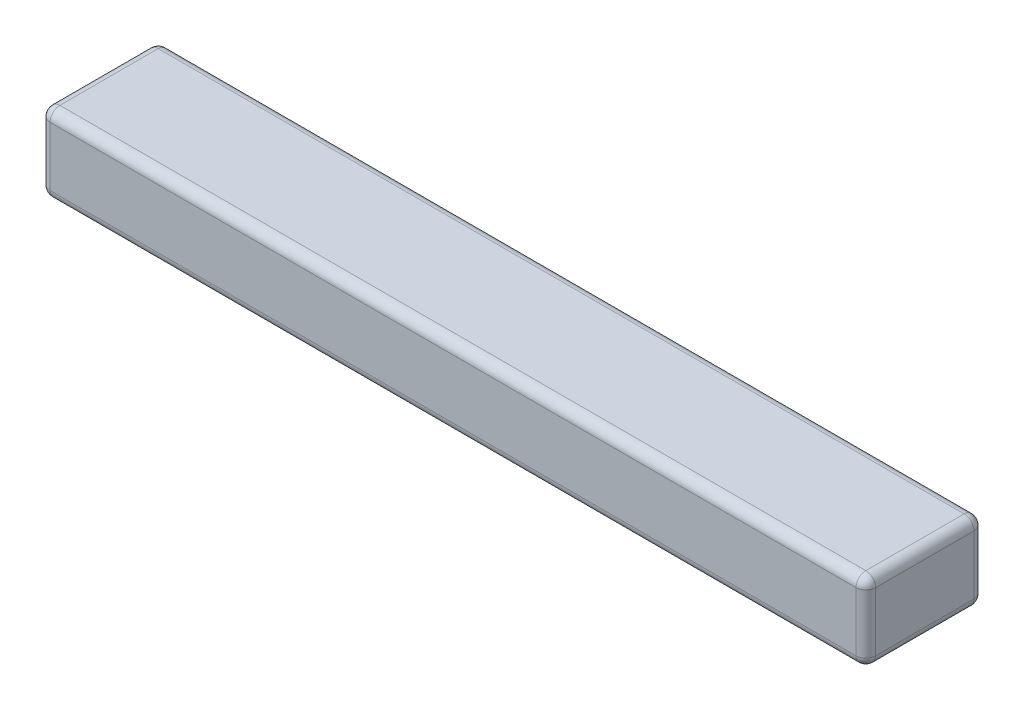
SolidWorks part; units mm, degrees
ref_plane "Front Plane" through (0, 0, 0) normal (0, 0, 1) x (1, 0, 0)
ref_plane "Top Plane" through (0, 0, 0) normal (0, 1, 0) x (1, 0, 0)
ref_plane "Right Plane" through (0, 0, 0) normal (1, 0, 0) x (0, 0, -1)
sketch "Sketch1" plane through (0, 0, 0) normal (1, 0, 0) x (0, 0, -1)
  line L1 (-30, -20) -> (30, -20)
  line L2 (-30, -20) -> (-30, 20)
  line L3 (-30, 20) -> (30, 20)
  line L4 (30, -20) -> (30, 20)
  line L5 (-30, -20) -> (30, 20) construction
  line L6 (-30, 20) -> (30, -20) construction
  point P0 (0, 0)
  dimension "D1" = 60
  dimension "D2" = 40
extrude "Boss-Extrude1" add sketch "Sketch1" along normal mid plane 420
fillet "Fillet1" radius 5 12 edges at (-210, -20, 0) (-210, 0, -30) (-210, 20, 0) (-210, 0, 30) (210, 0, -30) (210, 20, 0) (210, -20, 0) (210, 0, 30) (0, -20, -30) (0, 20, -30) (0, -20, 30) (0, 20, 30)
sketch "Sketch2" plane through (0, 20, 0) normal (0, 1, 0) x (1, 0, 0)
  line L0 (-100, 25) -> (-100, -25) construction
  line L1 (205, 25) -> (-205, 25) construction
  line L2 (-205, -25) -> (205, -25) construction
  line L3 (100, 25) -> (100, -25) construction
  line L4 (-210, -25) -> (-210, 25) construction
  line L5 (210, 25) -> (210, -25) construction
  dimension "D1" = 110
  dimension "D2" = 110
